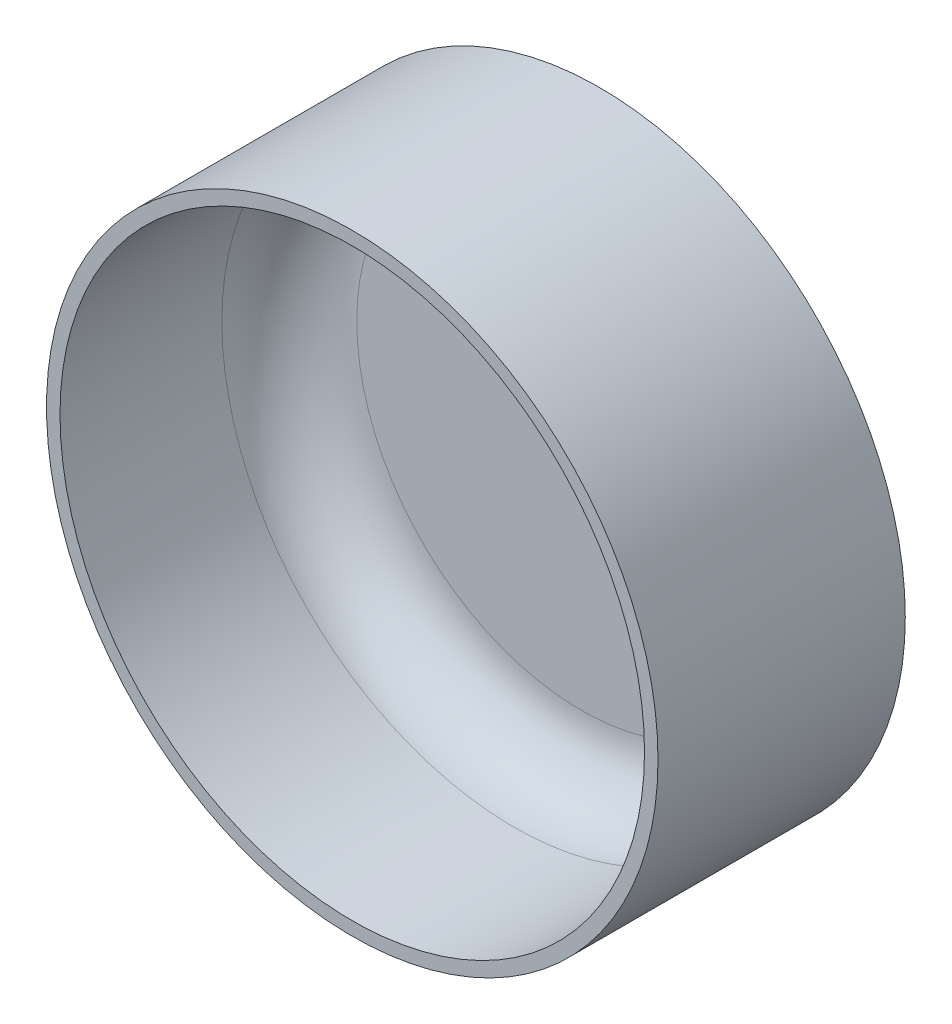
SolidWorks part; units mm, degrees
ref_plane "前视基准面" through (0, 0, 0) normal (0, 0, 1) x (1, 0, 0)
ref_plane "上视基准面" through (0, 0, 0) normal (0, 1, 0) x (1, 0, 0)
ref_plane "右视基准面" through (0, 0, 0) normal (1, 0, 0) x (0, 0, -1)
other "Configuration Table"
sketch "草图1" plane through (0, 0, 0) normal (0, 0, 1) x (1, 0, 0)
  circle A0 centre (0, 0) radius 65
  dimension "D1" = 130
extrude "拉伸-薄壁1" add sketch "草图1" along normal blind 55 thin
sketch "草图2" plane through (0, 0, 0) normal (0, 0, -1) x (-1, 0, 0)
  circle A1 centre (0, 0) radius 68
  circle A2 centre (0, 0) radius 68
  dimension "D1" = 0
extrude "凸台-拉伸1" add sketch "草图2" against normal blind 4
fillet "圆角1" radius 15 1 edges at (-65, 0, 4)
sketch "草图3" plane through (0, 0, 0) normal (0, 0, -1) x (-1, 0, 0)
  line L0 (0, 68) -> (0, -68)
  line L1 (-68, 0) -> (68, 0)
  line L2 (-25, 73) -> (25, 73)
  line L3 (-25, 73) -> (-25, 63)
  line L4 (-25, 63) -> (25, 63)
  line L5 (25, 73) -> (25, 63)
  line L6 (-25, 73) -> (25, 63) construction
  line L7 (-25, 63) -> (25, 73) construction
  line L8 (-25, -63) -> (25, -63)
  line L9 (25, -73) -> (25, -63)
  line L10 (-25, -73) -> (25, -73)
  line L11 (-25, -73) -> (-25, -63)
  circle A0 centre (0, 0) radius 68 construction
  circle A2 centre (0, 0) radius 68
  circle A3 centre (0, 0) radius 68
  dimension "D1" = 50
  dimension "D2" = 10
  dimension "D3" = 0
